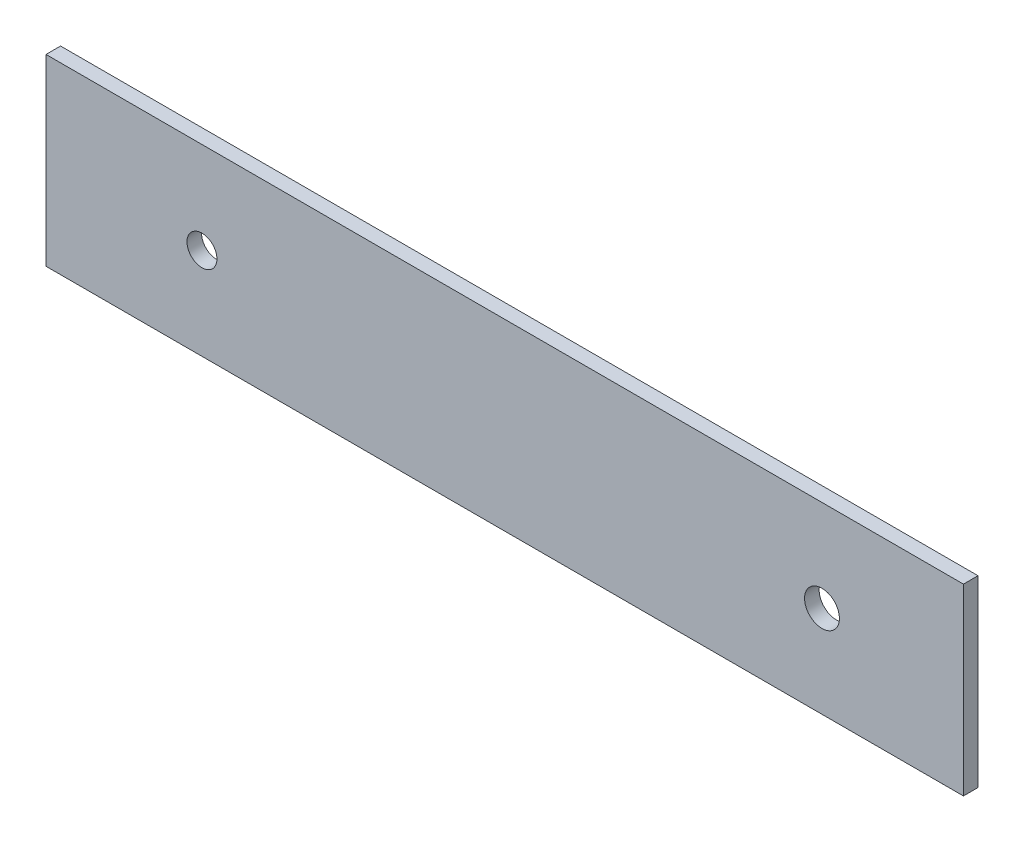
SolidWorks part; units mm, degrees
ref_plane "Front Plane" through (0, 0, 0) normal (0, 0, 1) x (1, 0, 0)
ref_plane "Top Plane" through (0, 0, 0) normal (0, 1, 0) x (1, 0, 0)
ref_plane "Right Plane" through (0, 0, 0) normal (1, 0, 0) x (0, 0, -1)
sketch "Sketch1" plane through (0, 0, 0) normal (0, 0, 1) x (1, 0, 0)
  line L1 (-50, 0) -> (50, 0)
  line L2 (-50, 0) -> (-50, 20)
  line L3 (-50, 20) -> (50, 20)
  line L4 (50, 0) -> (50, 20)
  dimension "D1" = 100
  dimension "D2" = 20
extrude "Boss-Extrude1" add sketch "Sketch1" along normal blind 1.5875
hole_wizard "#4 Clearance Hole1" positions "Sketch3" profile "Sketch2" hole size "#4" standard "ANSI Inch" end condition through all
sketch "Sketch3" plane through (0, 0, 1.5875) normal (0, 0, 1) x (1, 0, 0)
  line L0 (-50, 20) -> (-50, 0) construction
  point P0 (-33, 10)
  dimension "D1" = 10
  dimension "D2" = 17
sketch "Sketch2" plane through (-33, 10, 1.5875) normal (1, 0, 0) x (0, -1, 0)
  line L0 (0, 0) -> (0, 1.5875)
  line L1 (0, 1.5875) -> (1.6319, 1.5875)
  line L2 (1.6319, 1.5875) -> (1.6319, 0)
  line L5 (1.6319, 0) -> (0, 0)
  line L11 (0, -6.35) -> (0, 107.95) construction
  dimension "Thru Hole Dia." = 3.2639
  dimension "Thru Hole Depth" = 1.5875
hole_wizard "#6 Clearance Hole1" positions "Sketch5" profile "Sketch4" hole size "#6" standard "ANSI Inch" end condition through all
sketch "Sketch5" plane through (0, 0, 1.5875) normal (0, 0, 1) x (1, 0, 0)
  line L0 (-50, 0) -> (50, 0) construction
  circle A0 centre (-33, 10) radius 1.632 construction
  point P0 (34.58, 10)
  point P5 (0, 0)
  dimension "D1" = 67.58
  dimension "D2" = 10
sketch "Sketch4" plane through (34.58, 10, 1.5875) normal (1, 0, 0) x (0, -1, 0)
  line L0 (0, 0) -> (0, 1.5875)
  line L1 (0, 1.5875) -> (1.8986, 1.5875)
  line L2 (1.8986, 1.5875) -> (1.8986, 0)
  line L5 (1.8986, 0) -> (0, 0)
  line L11 (0, -6.35) -> (0, 107.95) construction
  dimension "Thru Hole Dia." = 3.7973
  dimension "Thru Hole Depth" = 1.5875
